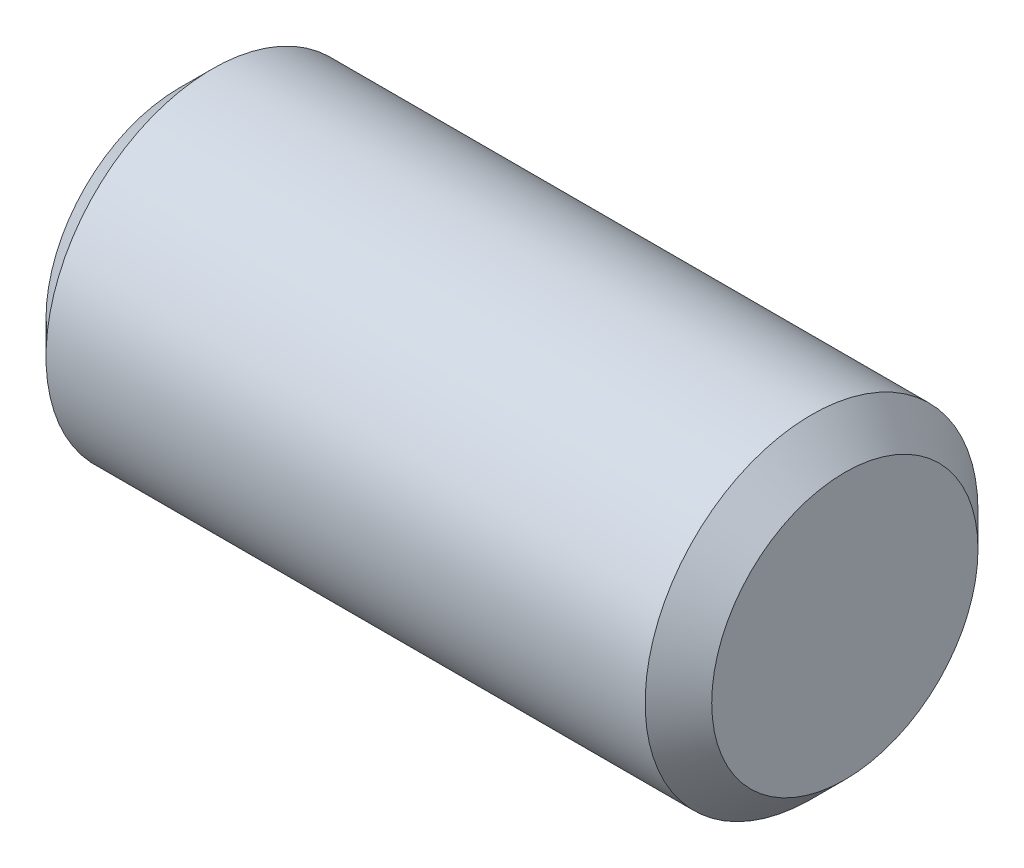
SolidWorks part; units mm, degrees
ref_plane "Front Plane" through (0, 0, 0) normal (0, 0, 1) x (1, 0, 0)
ref_plane "Top Plane" through (0, 0, 0) normal (0, 1, 0) x (1, 0, 0)
ref_plane "Right Plane" through (0, 0, 0) normal (1, 0, 0) x (0, 0, -1)
sketch "Sketch1" plane through (0, 0, 0) normal (1, 0, 0) x (0, 0, -1)
  line L0 (-6, 0) -> (6, 0) construction
  line L1 (0, 3) -> (0, -3) construction
  circle A0 centre (0, 0) radius 3 construction
  point P4 (0, 0)
  point P5 (0, 0)
  dimension "Diameter" = 6
  dimension "Length" = 12
sketch "Sketch2" plane through (0, 0, 0) normal (1, 0, 0) x (0, 0, -1)
  circle A1 centre (0, 0) radius 3 construction
  circle A2 centre (0, 0) radius 3
extrude "Boss-Extrude1" add sketch "Sketch2" against normal mid plane 12
chamfer "Chamfer2" distance 0.6 angle 45 2 edges at (-6, 0, -3) (6, 0, -3)
equation "\"D1@Chamfer2\"=\"Diameter@Sketch1\"*.1"
equation "\"D1@Boss-Extrude1\"=\"Length@Sketch1\""
